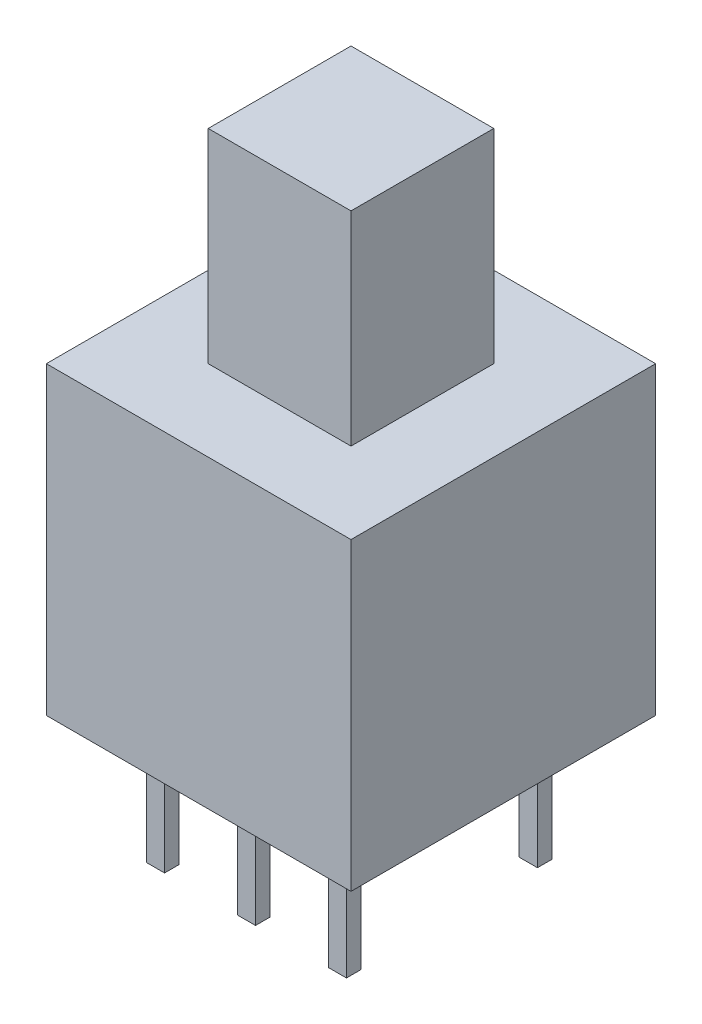
SolidWorks part; units mm, degrees
ref_plane "Front Plane" through (0, 0, 0) normal (0, 0, 1) x (1, 0, 0)
ref_plane "Top Plane" through (0, 0, 0) normal (0, 1, 0) x (1, 0, 0)
ref_plane "Right Plane" through (0, 0, 0) normal (1, 0, 0) x (0, 0, -1)
sketch "Sketch1" plane through (0, 0, 0) normal (0, 1, 0) x (1, 0, 0)
  line L1 (0, 0) -> (8.509, 0)
  line L2 (0, 0) -> (0, 8.509)
  line L3 (0, 8.509) -> (8.509, 8.509)
  line L4 (8.509, 0) -> (8.509, 8.509)
  dimension "D1" = 8.509
  dimension "D2" = 8.509
extrude "Boss-Extrude1" add sketch "Sketch1" along normal blind 8.509
sketch "Sketch2" plane through (0, 8.509, 0) normal (0, 1, 0) x (1, 0, 0)
  line L1 (2.2606, 6.2484) -> (6.2484, 6.2484)
  line L2 (2.2606, 6.2484) -> (2.2606, 2.2606)
  line L3 (2.2606, 2.2606) -> (6.2484, 2.2606)
  line L4 (6.2484, 6.2484) -> (6.2484, 2.2606)
  line L5 (2.2606, 4.2545) -> (6.2484, 4.2545) construction
  line L6 (4.2545, 6.2484) -> (4.2545, 2.2606) construction
  line L8 (8.509, 8.509) -> (0, 8.509) construction
  line L9 (0, 0) -> (8.509, 0) construction
  line L10 (0, 8.509) -> (0, 0) construction
  line L11 (8.509, 0) -> (8.509, 8.509) construction
  dimension "D1" = 3.9878
  dimension "D2" = 3.9878
extrude "Boss-Extrude2" add sketch "Sketch2" along normal blind 5.6896
sketch "Sketch3" plane through (0, 0, 0) normal (0, -1, 0) x (1, 0, 0)
  line L1 (1.4478, -1.3462) -> (1.9558, -1.3462)
  line L2 (1.4478, -1.3462) -> (1.4478, -1.7526)
  line L3 (1.4478, -1.7526) -> (1.9558, -1.7526)
  line L4 (1.9558, -1.3462) -> (1.9558, -1.7526)
  line L10 (1.4478, -6.6802) -> (1.4478, -7.0866)
  line L11 (1.4478, -6.6802) -> (1.9558, -6.6802)
  line L12 (1.9558, -6.6802) -> (1.9558, -7.0866)
  line L13 (1.4478, -7.0866) -> (1.9558, -7.0866)
  line L14 (3.9878, -6.6802) -> (3.9878, -7.0866)
  line L15 (3.9878, -6.6802) -> (4.4958, -6.6802)
  line L16 (4.4958, -6.6802) -> (4.4958, -7.0866)
  line L17 (3.9878, -7.0866) -> (4.4958, -7.0866)
  line L18 (6.5278, -6.6802) -> (6.5278, -7.0866)
  line L19 (6.5278, -6.6802) -> (7.0358, -6.6802)
  line L20 (7.0358, -6.6802) -> (7.0358, -7.0866)
  line L21 (6.5278, -7.0866) -> (7.0358, -7.0866)
  line L22 (3.9878, -1.3462) -> (3.9878, -1.7526)
  line L23 (3.9878, -1.3462) -> (4.4958, -1.3462)
  line L24 (4.4958, -1.3462) -> (4.4958, -1.7526)
  line L25 (3.9878, -1.7526) -> (4.4958, -1.7526)
  line L26 (6.5278, -1.3462) -> (6.5278, -1.7526)
  line L27 (6.5278, -1.3462) -> (7.0358, -1.3462)
  line L28 (7.0358, -1.3462) -> (7.0358, -1.7526)
  line L29 (6.5278, -1.7526) -> (7.0358, -1.7526)
  line L31 (1.4478, -1.5494) -> (1.9558, -1.5494) construction
  line L32 (1.7018, -1.3462) -> (1.7018, -1.7526) construction
  line L33 (0, -8.509) -> (0, 0) construction
  line L34 (0, 0) -> (8.509, 0) construction
  dimension "D1" = 0.4064
  dimension "D2" = 0.508
  dimension "D3" = 1.7018
  dimension "D4" = 1.5494
  dimension "D5" = 2
  dimension "D6" = 3
extrude "Boss-Extrude3" add sketch "Sketch3" along normal blind 3.5052
